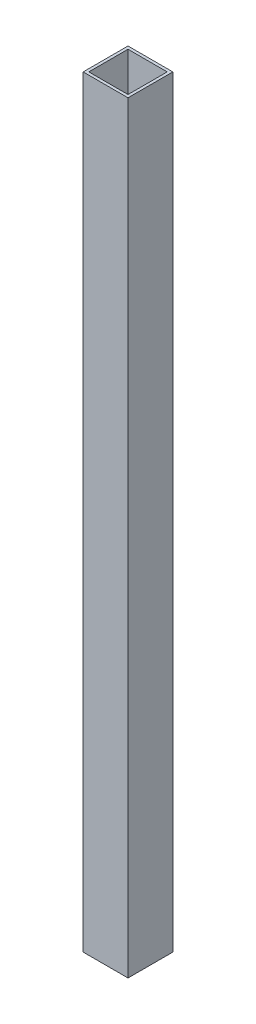
SolidWorks part; units mm, degrees
material "6061 Alloy"
ref_plane "Front Plane" through (0, 0, 0) normal (0, 0, 1) x (1, 0, 0)
ref_plane "Top Plane" through (0, 0, 0) normal (0, 1, 0) x (1, 0, 0)
ref_plane "Right Plane" through (0, 0, 0) normal (1, 0, 0) x (0, 0, -1)
sketch "Sketch1" plane through (0, 0, 0) normal (0, 1, 0) x (1, 0, 0)
  line L1 (12.7, 12.7) -> (-12.7, 12.7)
  line L2 (12.7, 12.7) -> (12.7, -12.7)
  line L3 (12.7, -12.7) -> (-12.7, -12.7)
  line L4 (-12.7, 12.7) -> (-12.7, -12.7)
  line L5 (12.7, 12.7) -> (-12.7, -12.7) construction
  line L6 (12.7, -12.7) -> (-12.7, 12.7) construction
  line L7 (11.1125, 11.1125) -> (-11.1125, 11.1125)
  line L8 (11.1125, 11.1125) -> (11.1125, -11.1125)
  line L9 (11.1125, -11.1125) -> (-11.1125, -11.1125)
  line L10 (-11.1125, 11.1125) -> (-11.1125, -11.1125)
  line L11 (11.1125, 11.1125) -> (-11.1125, -11.1125) construction
  line L12 (11.1125, -11.1125) -> (-11.1125, 11.1125) construction
  point P0 (0, 0)
  point P6 (0, 0)
  dimension "D1" = 25.4
  dimension "D2" = 25.4
  dimension "D3" = 1.5875
  dimension "D4" = 1.5875
extrude "Boss-Extrude1" add sketch "Sketch1" along normal blind 431.8
